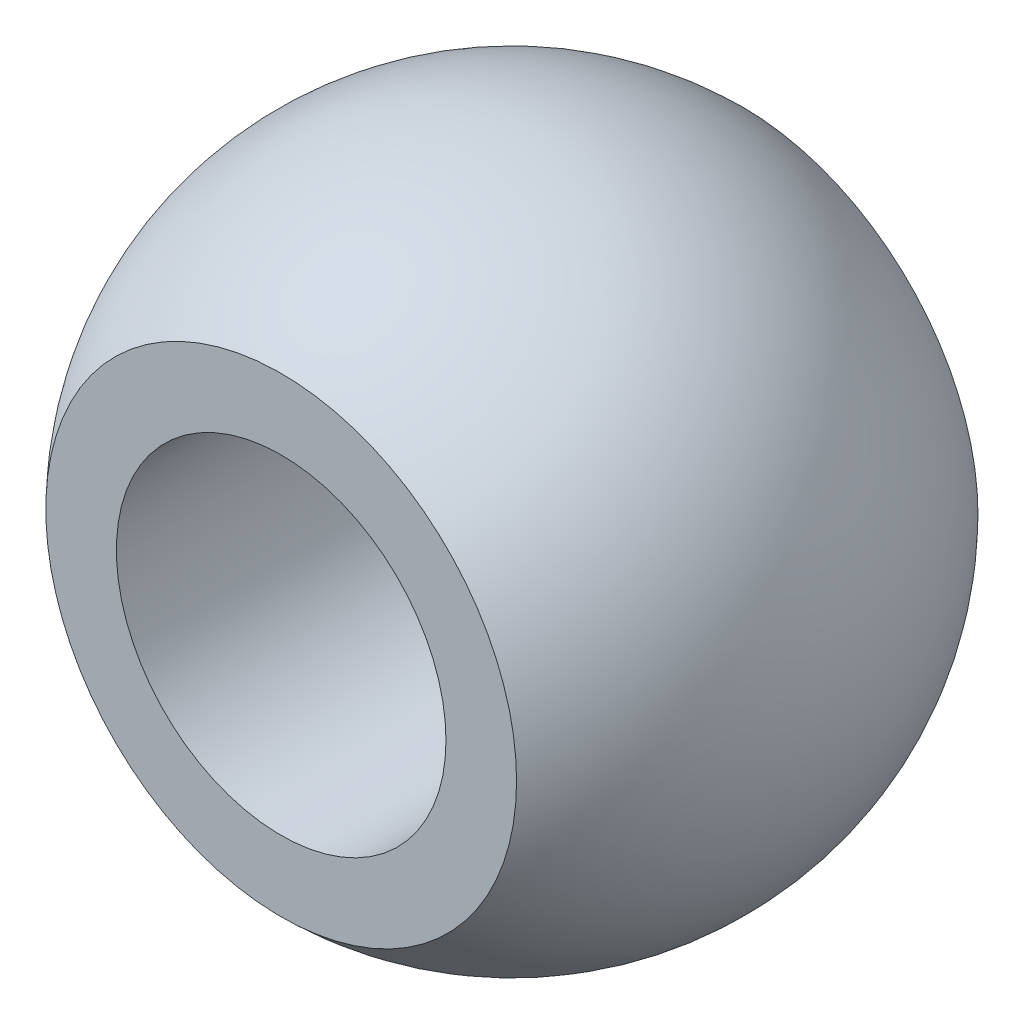
SolidWorks part; units mm, degrees
material "Alloy Steel"
ref_plane "Front Plane" through (0, 0, 0) normal (0, 0, 1) x (1, 0, 0)
ref_plane "Top Plane" through (0, 0, 0) normal (0, 1, 0) x (1, 0, 0)
ref_plane "Right Plane" through (0, 0, 0) normal (1, 0, 0) x (0, 0, -1)
sketch "Sketch1" plane through (0, 0, 0) normal (0, 0, 1) x (1, 0, 0)
  line L0 (0, -7.9375) -> (0, 7.9375) construction
  line L1 (0, 7.9375) -> (0, -7.9375)
  arc A0 (0, 7.9375) -> (0, -7.9375) centre (0, 0) cw
  dimension "D1" = 7.9375
revolve "Revolve1" add sketch "Sketch1" angle 360 about L0
sketch "Sketch2" plane through (0, 0, 0) normal (0, 0, 1) x (1, 0, 0)
  circle A0 centre (0, 0) radius 3.9688
  dimension "D1" = 7.9375
extrude "Extrude1" cut sketch "Sketch2" against normal mid plane 50.8
ref_plane "Plane1" through (0, 0, 5.5562) normal (0, 0, 1) x (1, 0, 0)
sketch "Sketch3" plane through (0, 0, 5.5562) normal (0, 0, 1) x (1, 0, 0)
  circle A0 centre (0, 0) radius 7.9375 construction
  circle A1 centre (0, 0) radius 7.9375
extrude "Extrude2" cut sketch "Sketch3" along normal up to next
mirror "Mirror1" about plane through (0, 0, 0) normal (0, 0, 1) of "Extrude2"
